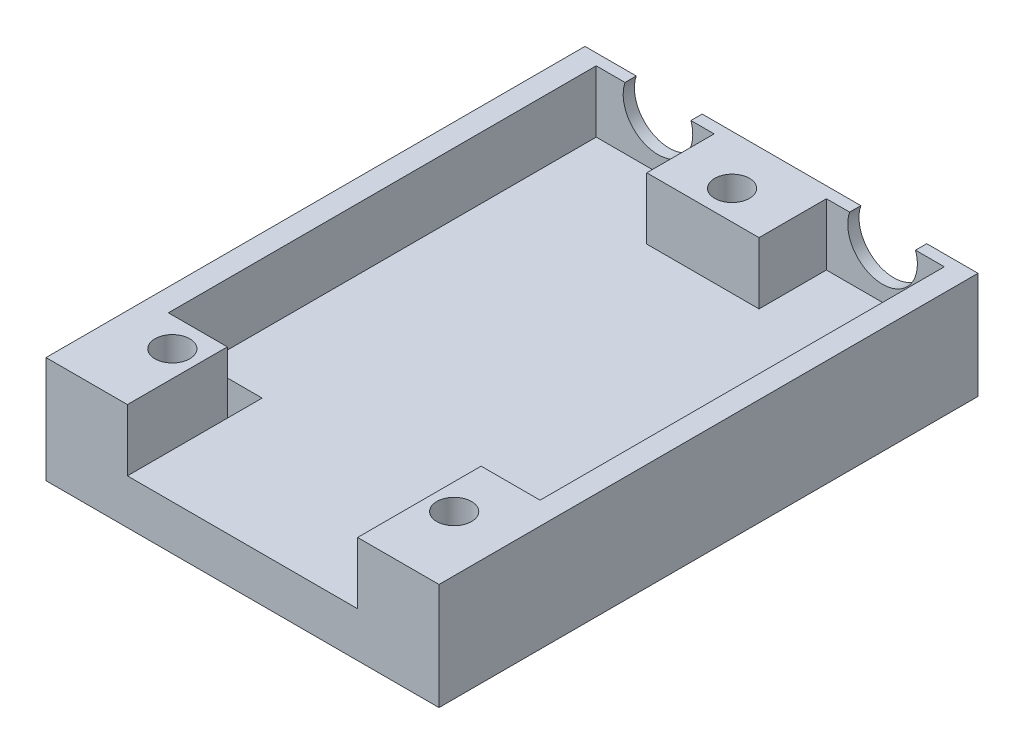
SolidWorks part; units mm, degrees
ref_plane "Front Plane" through (0, 0, 0) normal (0, 0, 1) x (1, 0, 0)
ref_plane "Top Plane" through (0, 0, 0) normal (0, 1, 0) x (1, 0, 0)
ref_plane "Right Plane" through (0, 0, 0) normal (1, 0, 0) x (0, 0, -1)
sketch "Sketch1" plane through (0, 0, 0) normal (0, 1, 0) x (1, 0, 0)
  line L1 (-17.5, 24) -> (17.5, 24)
  line L2 (-17.5, 24) -> (-17.5, -24)
  line L3 (-17.5, -24) -> (17.5, -24)
  line L4 (17.5, 24) -> (17.5, -24)
  line L5 (-44.2539, 0) -> (44.2539, 0) construction
  line L6 (0, -44.7868) -> (0, 44.7868) construction
  dimension "D2" = 35
  dimension "D1" = 48
  dimension "D3" = 24
  dimension "D4" = 17.5
extrude "Boss-Extrude1" add sketch "Sketch1" along normal blind 4
sketch "Sketch2" plane through (0, 4, 0) normal (0, 1, 0) x (1, 0, 0)
  line L1 (-15.5, 23) -> (15.5, 23)
  line L2 (-15.5, 23) -> (-15.5, -21)
  line L3 (-15.5, -21) -> (15.5, -21)
  line L4 (15.5, 23) -> (15.5, -21)
  line L6 (17.5, -24) -> (17.5, 24) construction
  line L7 (-17.5, -24) -> (17.5, -24) construction
  line M5 (-17.5, 24) -> (-17.5, -24)
  line M6 (-17.5, -24) -> (17.5, -24)
  line M7 (17.5, -24) -> (17.5, 24)
  line M8 (17.5, 24) -> (-17.5, 24)
  dimension "D1" = 2
  dimension "D2" = 3
  dimension "D3" = 31
  dimension "D4" = 44
extrude "Boss-Extrude2" add sketch "Sketch2" along normal blind 5.5 contours L1 L4 L3 L2 M8 M5 M6 M7
sketch "Sketch3" plane through (0, 4, 0) normal (0, 1, 0) x (1, 0, 0)
  line L0 (-15.5, 23) -> (15.5, 23) construction
  line L1 (-5, 23) -> (5, 23)
  line L2 (-5, 23) -> (-5, 17)
  line L3 (-5, 17) -> (5, 17)
  line L4 (5, 23) -> (5, 17)
  line L5 (15.5, 23) -> (15.5, -21) construction
  line L7 (-15.5, -21) -> (-10.25, -21)
  line L8 (-15.5, -21) -> (-15.5, -13)
  line L9 (-15.5, -13) -> (-10.25, -13)
  line L10 (-10.25, -21) -> (-10.25, -13)
  line L11 (15.5, -21) -> (10.25, -21)
  line L12 (15.5, -21) -> (15.5, -13)
  line L13 (15.5, -13) -> (10.25, -13)
  line L14 (10.25, -21) -> (10.25, -13)
  dimension "D1" = 10
  dimension "D2" = 6
  dimension "D3" = 10.5
  dimension "D4" = 5.25
  dimension "D5" = 5.25
  dimension "D6" = 8
  dimension "D7" = 8
extrude "Boss-Extrude3" add sketch "Sketch3" along normal blind 5.5
sketch "Sketch4" plane through (0, 0, 24) normal (0, 0, 1) x (1, 0, 0)
  line L0 (-17.5, 9.5) -> (17.5, 9.5) construction
  line L1 (-10.25, 9.5) -> (10.25, 9.5)
  line L2 (-10.25, 9.5) -> (-10.25, 4)
  line L3 (-10.25, 4) -> (10.25, 4)
  line L4 (10.25, 9.5) -> (10.25, 4)
  line L5 (-17.5, 9.5) -> (-17.5, 0) construction
  line L6 (17.5, 9.5) -> (17.5, 0) construction
  dimension "D1" = 7.25
  dimension "D2" = 7.25
  dimension "D3" = 5.5
extrude "Cut-Extrude1" cut sketch "Sketch4" against normal up to surface (3 mm away) up to face at (0, 6.75, 21)
sketch "Sketch5" plane through (0, 0, 0) normal (0, -1, 0) x (1, 0, 0)
  line L0 (44.2539, 0) -> (-44.2539, 0) construction
  line L1 (-2.55, 8.6) -> (2.45, 8.6)
  line L2 (-2.55, 8.6) -> (-2.55, 3.6)
  line L3 (-2.55, 3.6) -> (2.45, 3.6)
  line L4 (2.45, 8.6) -> (2.45, 3.6)
  line L5 (-2.55, -3.6) -> (2.45, -3.6)
  line L6 (-2.55, -3.6) -> (-2.55, -8.6)
  line L7 (-2.55, -8.6) -> (2.45, -8.6)
  line L8 (2.45, -3.6) -> (2.45, -8.6)
  line L9 (17.5, 24) -> (17.5, -24) construction
  dimension "D1" = 5
  dimension "D2" = 7.2
  dimension "D3" = 3.6
  dimension "D4" = 15.05
  dimension "D5" = 15.05
sketch "Sketch6" plane through (0, 0, -24) normal (0, 0, -1) x (-1, 0, 0)
  line L0 (-17.5, 9.5) -> (17.5, 9.5) construction
  line L3 (-17.5, 9.5) -> (-17.5, 0) construction
  arc A0 (-7.0657, 9.5) -> (-12.9343, 9.5) centre (-10, 8.5) cw
  arc A1 (12.9343, 9.5) -> (7.0657, 9.5) centre (10, 8.5) cw
  line M3 (17.5, 9.5) -> (-17.5, 9.5)
  dimension "D1" = 20
  dimension "D3" = 3.1
  dimension "D4" = 3.1
  dimension "D2" = 7.5
  dimension "D5" = 1
  dimension "D6" = 1
extrude "Cut-Extrude2" cut sketch "Sketch6" against normal blind 2 contours A0 M3 | A1 M3
sketch "Sketch7" plane through (0, 9.5, 0) normal (0, 1, 0) x (1, 0, 0)
  line L1 (-15.5, -12) -> (-10.25, -12)
  line L2 (-15.5, -12) -> (-15.5, -15.1)
  line L3 (-15.5, -15.1) -> (-10.25, -15.1)
  line L4 (-10.25, -12) -> (-10.25, -15.1)
  line L5 (-10.25, -24) -> (-10.25, -13) construction
  line L6 (-17.5, -24) -> (-10.25, -24) construction
  dimension "D1" = 3.1
  dimension "D2" = 5.25
  dimension "D3" = 8.9
extrude "Cut-Extrude3" cut sketch "Sketch7" against normal up to surface (9.5 mm away) up to face at (0, 0, 0)
sketch "Sketch8" plane through (0, 0, 0) normal (0, 1, 0) x (1, 0, 0)
  line L0 (0, -44.7868) -> (0, 44.7868) construction
  line L1 (10.25, -24) -> (17.5, -24) construction
  line L2 (7.0657, 24) -> (-7.0657, 24) construction
  line L4 (-17.5, -24) -> (-10.25, -24) construction
  circle A0 centre (-12.55, -17.7) radius 1.55
  circle A1 centre (12.55, -17.7) radius 1.55
  circle A2 centre (0, 19.6) radius 1.55
  dimension "D1" = 3.1
  dimension "D7" = 3.1
  dimension "D8" = 3.1
  dimension "D2" = 6.3
  dimension "D3" = 25.1
  dimension "D4" = 6.3
  dimension "D5" = 12.55
  dimension "D6" = 4.4
extrude "Cut-Extrude4" cut sketch "Sketch8" along direction (0, 1, 0) on the side against the normal blind 5.5 from surface at 9.5 starting at face at (-14.0461, 9.5, -1.975)
sketch "Sketch9" plane through (0, 0, 0) normal (0, 1, 0) x (1, 0, 0)
  line L0 (-35.1135, -20.6) -> (29.9959, -20.6) construction
  line L1 (-7.0657, 23) -> (-5, 23) construction
  line L2 (-35.1135, 21.9) -> (32.5575, 21.9) construction
  point P4 (-6.0329, 23)
  dimension "D1" = 43.6
  dimension "D2" = 42.5
extrude "Cut-Extrude5" cut sketch "Sketch5" against normal blind 2
equation "\"fWidth\"=35"
equation "\"D2@Sketch1\"=\"fWidth\""
equation "\"fLength\"= 48"
equation "\"D1@Sketch1\"=\"fLength\""
equation "\"D3@Sketch1\"=\"fLength\"/2"
equation "\"D4@Sketch1\"=\"fWidth\"/2"
equation "\"wThickness\"=2"
equation "\"D1@Sketch2\"=\"wThickness\""
equation "\"D3@Sketch2\"=\"fWidth\"- 2* \"wThickness\""
equation "\"D4@Sketch2\"=\"fLength\"- 2 *\"wThickness\""
equation "\"wHeight\"= 5.5"
equation "\"D1@Boss-Extrude2\"=\"wHeight\""
equation "\"D3@Sketch3\"=(\"fWidth\"- 2 *\"wThickness\" - 10)/2"
equation "\"D4@Sketch5\"=(\"fWidth\"- 4.9)/2"
equation "\"D5@Sketch5\"=(\"fWidth\"- 4.9)/2"
equation "\"D3@Sketch4\"=\"wHeight\""
